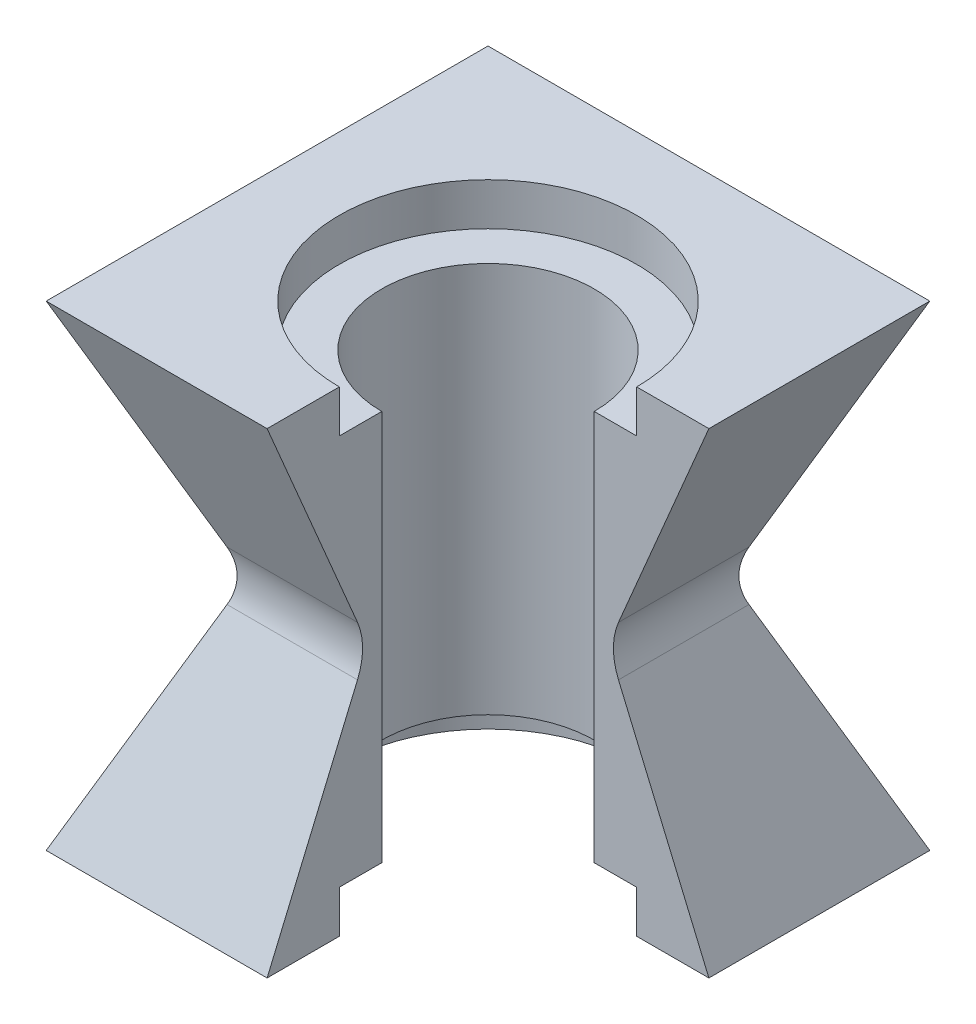
SolidWorks part; units mm, degrees
material "Acier inoxydable moulé"
ref_plane "Plan de face" through (0, 0, 0) normal (0, 0, 1) x (1, 0, 0)
ref_plane "Plan de dessus" through (0, 0, 0) normal (0, 1, 0) x (1, 0, 0)
ref_plane "Plan de droite" through (0, 0, 0) normal (1, 0, 0) x (0, 0, -1)
sketch "Esquisse1" plane through (0, 0, 0) normal (0, 1, 0) x (1, 0, 0)
  line L1 (-52, 52) -> (52, 52)
  line L2 (-52, 52) -> (-52, -52)
  line L3 (-52, -52) -> (52, -52)
  line L4 (52, 52) -> (52, -52)
  line L5 (-52, 52) -> (52, -52) construction
  line L6 (-52, -52) -> (52, 52) construction
  point P0 (0, 0)
  dimension "D1" = 104
  dimension "D2" = 104
extrude "Boss.-Extru.2" add sketch "Esquisse1" against normal blind 56 draft 23
mirror "Symétrie1" about plane through (0, -56, 0) normal (0, 1, 0) of "Boss.-Extru.2"
sketch "Esquisse2" plane through (0, 0, 0) normal (0, 1, 0) x (1, 0, 0)
  circle A0 centre (0, 0) radius 25
  dimension "D1" = 50
extrude "Enlèv. mat.-Extru.1" cut sketch "Esquisse2" against normal through all and the other way through all
fillet "Congé1" radius 15 4 edges at (0, -56, 28.2294) (28.2294, -56, 0) (0, -56, -28.2294) (-28.2294, -56, 0)
sketch "Esquisse3" plane through (0, 0, 0) normal (0, 1, 0) x (1, 0, 0)
  line L1 (52, -52) -> (0, -52)
  line L2 (52, -52) -> (52, 0)
  line L3 (52, 0) -> (0, 0)
  line L4 (0, -52) -> (0, 0)
extrude "Enlèv. mat.-Extru.2" cut sketch "Esquisse3" against normal through all
sketch "Esquisse4" plane through (0, 0, 0) normal (0, 1, 0) x (1, 0, 0)
  circle A0 centre (0, 0) radius 35
  dimension "D1" = 70
extrude "Enlèv. mat.-Extru.3" cut sketch "Esquisse4" against normal blind 10
ref_plane "Plan1" through (0, -56, 0) normal (0, 1, 0) x (1, 0, 0)
mirror "Symétrie2" about plane through (0, -56, 0) normal (0, 1, 0) of "Enlèv. mat.-Extru.3"
equation "\"A\"= 112"
equation "\"B\"= 104"
equation "\"C\"= 23"
equation "\"D1@Esquisse1\"=\"B\""
equation "\"D2@Esquisse1\"=\"B\""
equation "\"D1@Boss.-Extru.2\"=\"A\" / 2"
equation "\"D3@Boss.-Extru.2\"=\"C\""
